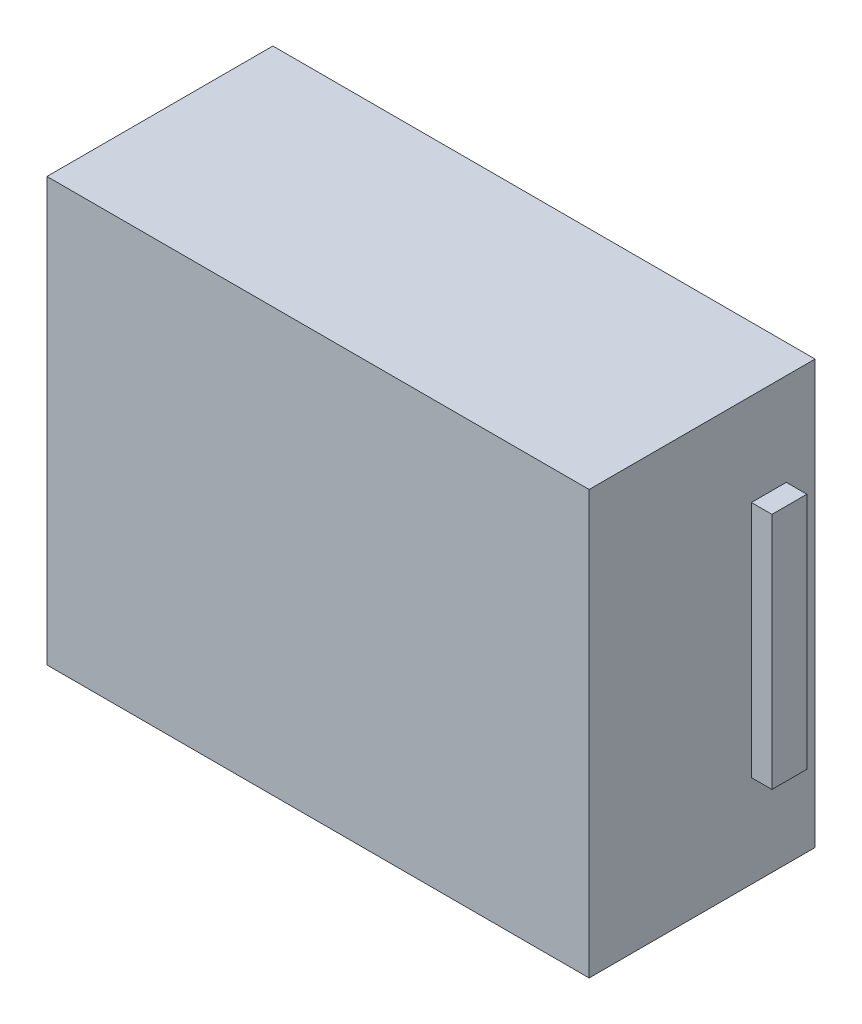
SolidWorks part; units mm, degrees
ref_plane "Front Plane" through (0, 0, 0) normal (0, 0, 1) x (1, 0, 0)
ref_plane "Top Plane" through (0, 0, 0) normal (0, 1, 0) x (1, 0, 0)
ref_plane "Right Plane" through (0, 0, 0) normal (1, 0, 0) x (0, 0, -1)
sketch "Sketch1" plane through (0, 0, 0) normal (0, 0, 1) x (1, 0, 0)
  line L1 (0, 0) -> (132, 0)
  line L2 (0, 0) -> (0, -103)
  line L3 (0, -103) -> (132, -103)
  line L4 (132, 0) -> (132, -103)
  dimension "D1" = 132
  dimension "D2" = 103
extrude "Boss-Extrude1" add sketch "Sketch1" along normal blind 55
sketch "Sketch2" plane through (132, 0, 0) normal (1, 0, 0) x (0, 0, -1)
  line L0 (0, -103) -> (0, 0) construction
  line L1 (-15.5, -22.5) -> (-7, -22.5)
  line L2 (-15.5, -22.5) -> (-15.5, -80.5)
  line L3 (-15.5, -80.5) -> (-7, -80.5)
  line L4 (-7, -22.5) -> (-7, -80.5)
  point P4 (0, -51.5)
  point P7 (-7, -51.5)
  dimension "D1" = 58
  dimension "D2" = 8.5
  dimension "D3" = 7
extrude "Boss-Extrude2" add sketch "Sketch2" along normal blind 5
sketch "Sketch3" plane through (0, 0, 0) normal (0, 0, -1) x (-1, 0, 0)
  line L0 (-132, -51.5) -> (0, -51.5) construction
  line L1 (-132, -103) -> (-132, 0) construction
  line L2 (0, 0) -> (0, -103) construction
  circle A2 centre (-106, -71.5) radius 2.5
  circle A3 centre (-26, -71.5) radius 2.5
  dimension "D6" = 5
  dimension "D7" = 5
  dimension "D8" = 80
  dimension "D9" = 20
  dimension "D10" = 26
